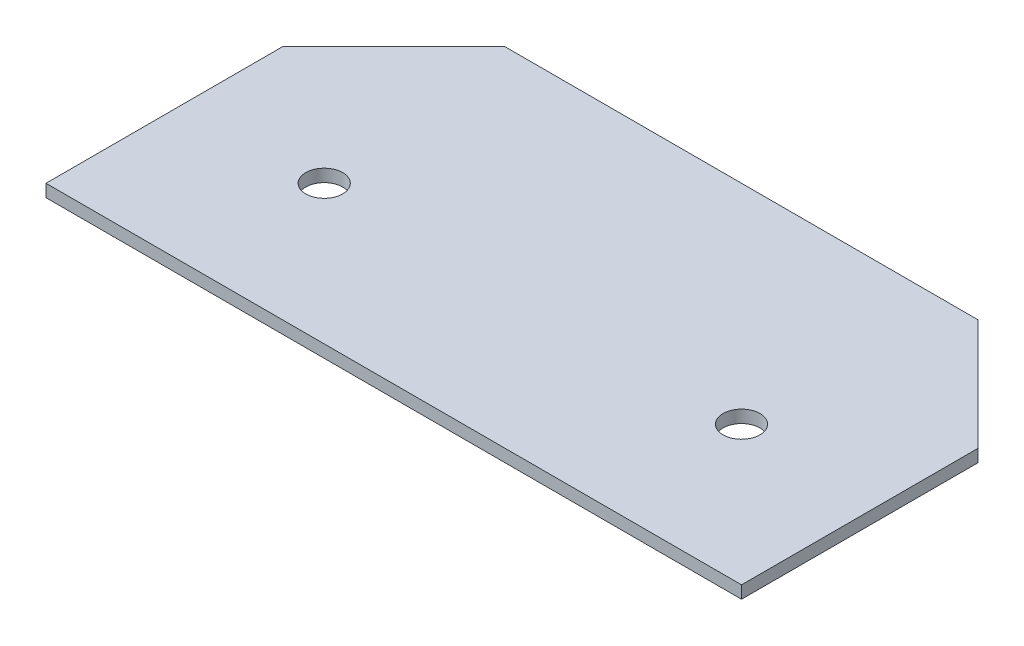
SolidWorks part; units mm, degrees
ref_plane "Front Plane" through (0, 0, 0) normal (0, 0, 1) x (1, 0, 0)
ref_plane "Top Plane" through (0, 0, 0) normal (0, 1, 0) x (1, 0, 0)
ref_plane "Right Plane" through (0, 0, 0) normal (1, 0, 0) x (0, 0, -1)
sketch "Sketch1" plane through (0, 0, 0) normal (0, 1, 0) x (1, 0, 0)
  line L1 (0, 0) -> (127, 0)
  line L2 (0, 0) -> (0, 63.5)
  line L3 (0, 63.5) -> (127, 63.5)
  line L4 (127, 0) -> (127, 63.5)
  dimension "D1" = 127
  dimension "D2" = 63.5
extrude "Boss-Extrude1" add sketch "Sketch1" along normal blind 2.286
sketch "Sketch2" plane through (0, 2.286, 0) normal (0, 1, 0) x (1, 0, 0)
  line L0 (0, 0) -> (127, 0) construction
  line L2 (0, 63.5) -> (0, 0) construction
  line L3 (127, 0) -> (127, 63.5) construction
  circle A0 centre (25.4, 25.4) radius 3.3734
  circle A1 centre (101.6, 25.4) radius 3.3734
  dimension "D1" = 25.4
  dimension "D2" = 25.4
  dimension "D3" = 25.4
  dimension "D4" = 6.7469
extrude "Cut-Extrude1" cut sketch "Sketch2" against normal through all
chamfer "Chamfer1" distance 20.32 angle 45 2 edges at (0, 1.143, -63.5) (127, 1.143, -63.5)
